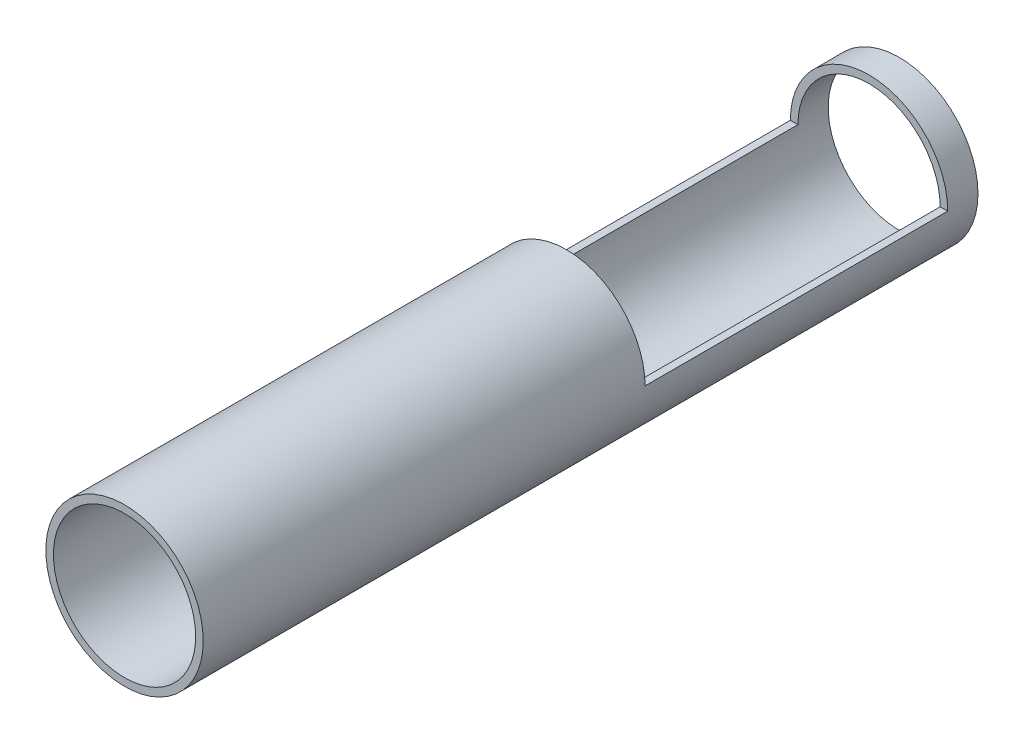
SolidWorks part; units mm, degrees
other "Elemento de detalle1"
other "Carpeta de soldadura"
ref_plane "Alzado" through (0, 0, 0) normal (0, 0, 1) x (1, 0, 0)
ref_plane "Planta" through (0, 0, 0) normal (0, 1, 0) x (1, 0, 0)
ref_plane "Vista lateral" through (0, 0, 0) normal (1, 0, 0) x (0, 0, -1)
sketch "Croquis1" plane through (0, 0, 0) normal (0, 0, 1) x (1, 0, 0)
  circle A0 centre (0, 0) radius 13
  circle A1 centre (0, 0) radius 11.75
  dimension "D1" = 26
  dimension "D2" = 23.5
extrude "Saliente-Extruir1" add sketch "Croquis1" along normal blind 128
sketch "Croquis2" plane through (0, 0, 0) normal (1, 0, 0) x (0, 0, -1)
  line L0 (-5, 17.6454) -> (-5, 0)
  line L1 (0, -13) -> (0, 13) construction
  line L2 (-5, 0) -> (-55, 0)
  line L3 (-55, 0) -> (-55, 17.6454)
  line L4 (-55, 17.6454) -> (-5, 17.6454)
  dimension "D1" = 5
  dimension "D2" = 50
extrude "Cortar-Extruir1" cut sketch "Croquis2" against normal through all both and the other way through all contours L4 L0 L2 L3
